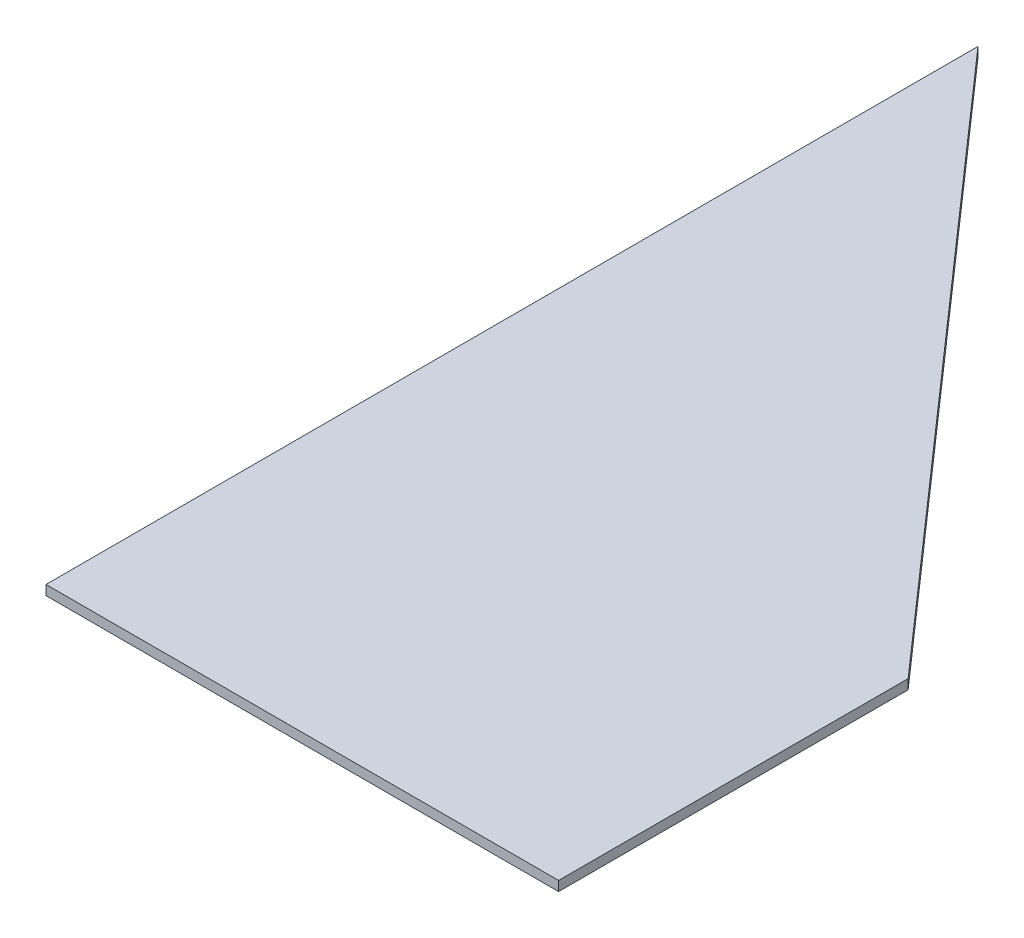
SolidWorks part; units mm, degrees
ref_plane "Front Plane" through (0, 0, 0) normal (0, 0, 1) x (1, 0, 0)
ref_plane "Top Plane" through (0, 0, 0) normal (0, 1, 0) x (1, 0, 0)
ref_plane "Right Plane" through (0, 0, 0) normal (1, 0, 0) x (0, 0, -1)
sketch "Sketch1" plane through (0, 0, 0) normal (0, 1, 0) x (1, 0, 0)
  line L0 (0, 0) -> (167.64, 0)
  line L1 (167.64, 0) -> (167.64, 114.3)
  line L2 (167.64, 114.3) -> (0, 304.8)
  line L3 (0, 304.8) -> (0, 0)
  dimension "D1" = 304.8
  dimension "D2" = 167.64
  dimension "D3" = 114.3
extrude "Boss-Extrude1" add sketch "Sketch1" along normal blind 3.175
